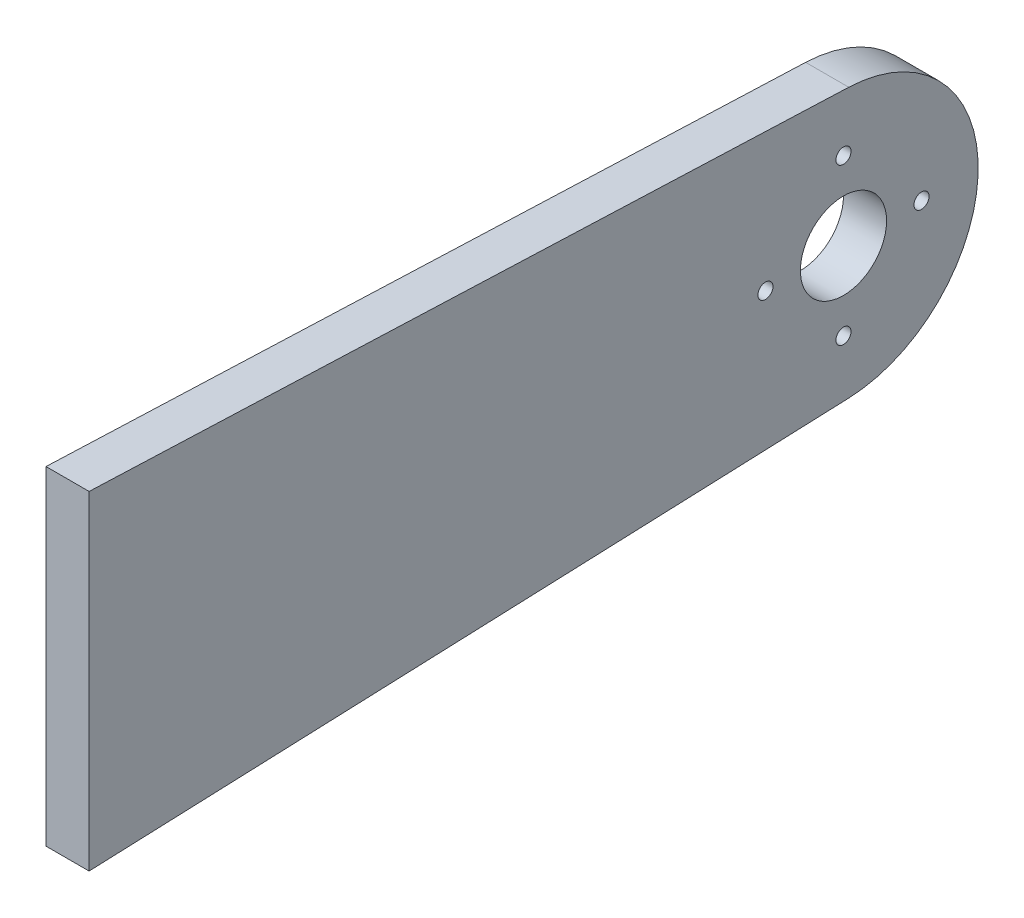
SolidWorks part; units mm, degrees
ref_plane "Front Plane" through (0, 0, 0) normal (0, 0, 1) x (1, 0, 0)
ref_plane "Top Plane" through (0, 0, 0) normal (0, 1, 0) x (1, 0, 0)
ref_plane "Right Plane" through (0, 0, 0) normal (1, 0, 0) x (0, 0, -1)
sketch "Sketch1" plane through (0, 0, 0) normal (1, 0, 0) x (0, 0, -1)
  line L0 (-70, 15.2548) -> (-70, -15.2548)
  line L19 (-70, 15.2548) -> (0.4898, 12.4904)
  line L20 (-70, -15.2548) -> (0.4898, -12.4904)
  circle A0 centre (0, 0) radius 4
  circle A1 centre (-7.24, 0) radius 0.7
  circle A2 centre (0, 7.24) radius 0.7
  circle A3 centre (7.24, 0) radius 0.7
  circle A4 centre (0, -7.24) radius 0.7
  arc A5 (0.4898, -12.4904) -> (0.4898, 12.4904) centre (0, 0) ccw
  point P18 (0, 0)
  dimension "D1" = 8
  dimension "D2" = 1.4
  dimension "D5" = 70
  dimension "D9" = 25
  dimension "D3" = 7.24
  dimension "D6" = 4.492
  dimension "D7" = 87.754
  dimension "D4" = 4
extrude "Boss-Extrude1" add sketch "Sketch1" along normal blind 4
sketch "Sketch2" plane through (4, 0, 0) normal (1, 0, 0) x (0, 0, -1)
  line L0 (0, 0) -> (-70, 0) construction
  line L1 (-70, 15.2548) -> (-70, -15.2548) construction
